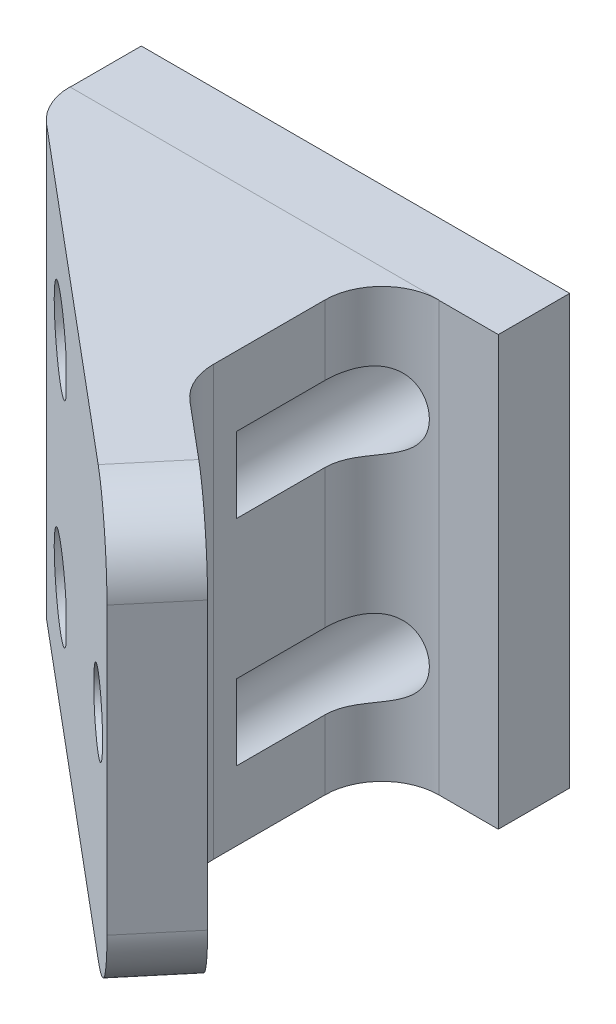
SolidWorks part; units mm, degrees
material "6061-T6 (SS)"
ref_plane "Front Plane" through (0, 0, 0) normal (0, 0, 1) x (1, 0, 0)
ref_plane "Top Plane" through (0, 0, 0) normal (0, 1, 0) x (1, 0, 0)
ref_plane "Right Plane" through (0, 0, 0) normal (1, 0, 0) x (0, 0, -1)
sketch "Sketch1" plane through (0, 0, 0) normal (0, 0, 1) x (1, 0, 0)
  line L1 (-9.525, -9.525) -> (9.525, -9.525)
  line L2 (-9.525, -9.525) -> (-9.525, 9.525)
  line L3 (-9.525, 9.525) -> (9.525, 9.525)
  line L4 (9.525, -9.525) -> (9.525, 9.525)
  line L5 (-9.525, -9.525) -> (9.525, 9.525) construction
  line L6 (-9.525, 9.525) -> (9.525, -9.525) construction
  circle A0 centre (-4.7625, 4.7625) radius 1.7272
  circle A1 centre (4.7625, 4.7625) radius 1.7272
  circle A2 centre (4.7625, -4.7625) radius 1.7272
  circle A3 centre (-4.7625, -4.7625) radius 1.7272
  point P0 (0, 0)
  dimension "D1" = 3.4544
  dimension "D2" = 19.05
  dimension "D3" = 19.05
  dimension "D4" = 9.525
extrude "Boss-Extrude1" add sketch "Sketch1" along normal blind 3.175
sketch "Sketch4" plane through (0, 0, 0) normal (0, 1, 0) x (1, 0, 0)
  line L1 (4.3494, -10.6723) -> (4.3494, -5.715)
  line L2 (-9.525, -3.175) -> (6.8894, -3.175)
  line L3 (9.525, -3.175) -> (-9.525, -3.175) construction
  line L6 (-8.6177, -5.1208) -> (8.0802, -19.1319)
  line L7 (8.0802, -19.1319) -> (10.1211, -16.6998)
  line L8 (10.1211, -16.6998) -> (5.2567, -12.6181)
  line L10 (-9.525, -3.175) -> (-9.525, 0) construction
  arc A0 (6.8894, -3.175) -> (4.3494, -5.715) centre (6.8894, -5.715) ccw
  arc A3 (4.3494, -10.6723) -> (5.2567, -12.6181) centre (6.8894, -10.6723) ccw
  arc A4 (-8.6177, -5.1208) -> (-9.525, -3.175) centre (-6.985, -3.175) cw
  point P9 (0, 0)
  point P19 (6.6684, -15.875)
  dimension "D1" = 3.175
  dimension "D3" = 2.54
  dimension "D4" = 6.35
  dimension "D2" = 40
  dimension "D5" = 3.175
  dimension "D6" = 1.5875
  dimension "D7" = 15.875
extrude "Boss-Extrude3" add sketch "Sketch4" along normal blind 9.5377 and the other way blind 9.525
sketch "Sketch5" plane through (-6.0821, 0, 7.2484) normal (-0.6428, 0, 0.766) x (0.766, 0, 0.6428)
  line L1 (18.4876, -9.525) -> (18.4876, 9.5377) construction
  circle A0 centre (15.3126, 0) radius 1.5875
  dimension "D1" = 3.175
  dimension "D2" = 3.175
fillet "Fillet3" radius 3.175 2 edges at (9.1006, -9.525, 17.9159) (9.1006, 9.5377, 17.9159)
extrude "Cut-Extrude1" cut sketch "Sketch5" against normal up to next
sketch "Sketch6" plane through (0, 0, 3.175) normal (0, 0, -1) x (-1, 0, 0)
  circle A0 centre (4.7625, -4.7625) radius 1.7272 construction
  circle A1 centre (4.7625, 4.7625) radius 1.7272 construction
  circle A4 centre (4.7625, -4.7625) radius 1.7272
  circle A5 centre (4.7625, 4.7625) radius 1.7272
  circle A8 centre (-4.7625, -4.7625) radius 1.7272 construction
  circle A9 centre (-4.7625, 4.7625) radius 1.7272 construction
  circle A10 centre (-4.7625, -4.7625) radius 1.7272
  circle A11 centre (-4.7625, 4.7625) radius 1.7272
extrude "Cut-Extrude2" cut sketch "Sketch6" against normal blind 6.477
